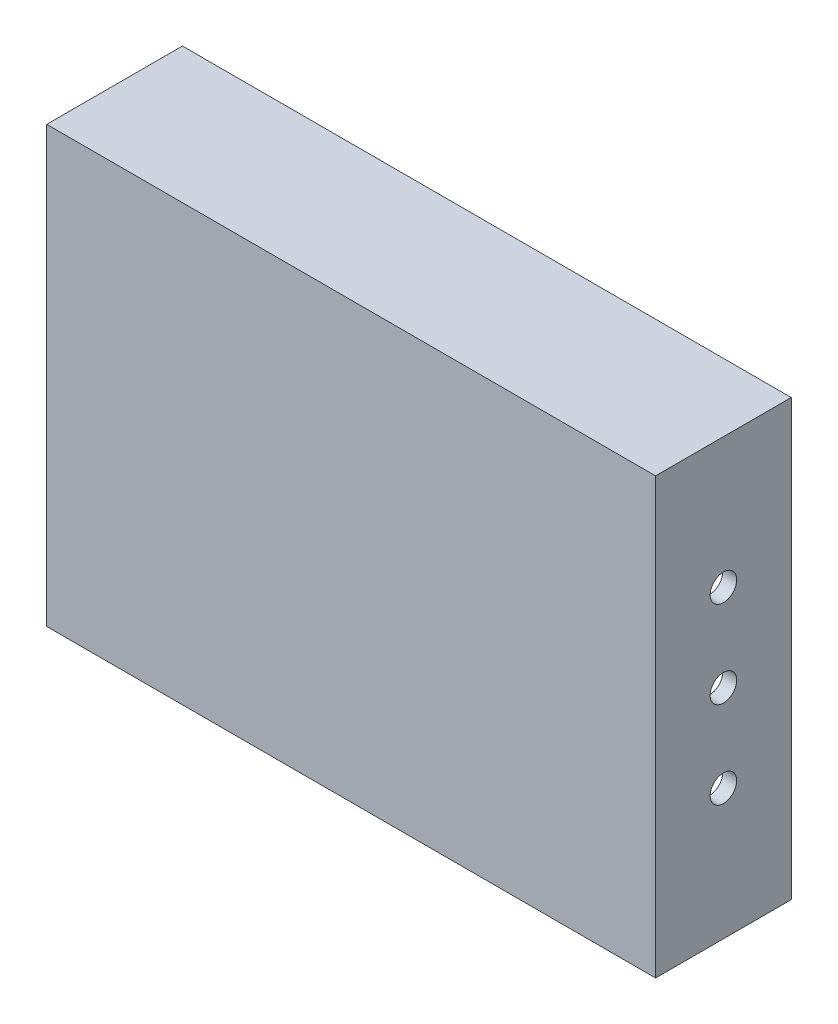
SolidWorks part; units mm, degrees
ref_plane "Front Plane" through (0, 0, 0) normal (0, 0, 1) x (1, 0, 0)
ref_plane "Top Plane" through (0, 0, 0) normal (0, 1, 0) x (1, 0, 0)
ref_plane "Right Plane" through (0, 0, 0) normal (1, 0, 0) x (0, 0, -1)
sketch "Sketch1" plane through (0, 0, 0) normal (0, 0, 1) x (1, 0, 0)
  line L0 (-93.5, 121) -> (-164, 121)
  line L1 (-175, 125) -> (0, 125)
  line L2 (-175, 125) -> (-175, 0)
  line L3 (-175, 0) -> (0, 0)
  line L4 (0, 125) -> (0, 0)
  line L5 (-11, 4) -> (-81.5, 4)
  line L6 (-4, 11) -> (-4, 114)
  line L7 (-11, 121) -> (-81.5, 121)
  line L8 (-171, 11) -> (-171, 114)
  line L11 (-171, 114) -> (-164, 114)
  line L12 (-164, 121) -> (-164, 114)
  line L15 (-171, 11) -> (-164, 11)
  line L16 (-164, 4) -> (-164, 11)
  line L19 (-4, 11) -> (-11, 11)
  line L20 (-11, 4) -> (-11, 11)
  line L23 (-4, 114) -> (-11, 114)
  line L24 (-11, 121) -> (-11, 114)
  line L26 (-93.5, 121) -> (-93.5, 114)
  line L27 (-93.5, 114) -> (-81.5, 114)
  line L28 (-81.5, 121) -> (-81.5, 114)
  line L30 (-93.5, 4) -> (-93.5, 11)
  line L31 (-93.5, 11) -> (-81.5, 11)
  line L32 (-81.5, 4) -> (-81.5, 11)
  line L33 (-93.5, 4) -> (-164, 4)
  dimension "D1" = 4
  dimension "D2" = 4
  dimension "D3" = 4
  dimension "D4" = 4
  dimension "D17" = 7
extrude "Boss-Extrude1" add sketch "Sketch1" along normal blind 35
sketch "Sketch2" plane through (0, 0, 35) normal (0, 0, 1) x (1, 0, 0)
  line L1 (-175, 125) -> (0, 125)
  line L2 (-175, 125) -> (-175, 0)
  line L3 (-175, 0) -> (0, 0)
  line L4 (0, 125) -> (0, 0)
extrude "Boss-Extrude2" add sketch "Sketch2" along normal blind 4
sketch "Sketch3" plane through (0, 0, 0) normal (0, 0, -1) x (-1, 0, 0)
  line L0 (0, 0) -> (0, 125) construction
  line L1 (0, 125) -> (175, 125) construction
  line L2 (175, 125) -> (175, 0) construction
  line L3 (175, 0) -> (0, 0) construction
  circle A0 centre (6, 119) radius 2.045
  circle A1 centre (87.5, 119) radius 2.045
  circle A2 centre (169, 119) radius 2.045
  circle A3 centre (169, 6) radius 2.045
  circle A4 centre (87.5, 6) radius 2.045
  circle A5 centre (6, 6) radius 2.045
  point P20 (87.5, 0)
  point P21 (87.5, 125)
  dimension "D1" = 4.09
  dimension "D4" = 4.09
  dimension "D7" = 4.09
  dimension "D10" = 4.09
  dimension "D13" = 4.09
  dimension "D14" = 4.09
  dimension "D2" = 6
  dimension "D3" = 6
  dimension "D5" = 6
  dimension "D6" = 6
  dimension "D8" = 6
  dimension "D9" = 6
  dimension "D11" = 6
  dimension "D12" = 6
  dimension "D15" = 6
  dimension "D16" = 6
extrude "Cut-Extrude1" cut sketch "Sketch3" against normal blind 6
sketch "Sketch4" plane through (0, 0, 0) normal (1, 0, 0) x (0, 0, -1)
  line L0 (-39, 125) -> (0, 125) construction
  line L1 (-39, 0) -> (-39, 125) construction
  circle A0 centre (-19.5, 87.5) radius 3.81
  circle A1 centre (-19.5, 62.5) radius 3.81
  circle A2 centre (-19.5, 37.5) radius 3.81
  point P6 (0, 0)
  point P9 (-19.5, 125)
  point P10 (0, 0)
  point P12 (-78.7424, 48.6819)
  point P14 (-39, 62.5)
  dimension "D1" = 7.62
  dimension "D2" = 7.62
  dimension "D3" = 7.62
  dimension "D4" = 25
  dimension "D5" = 25
extrude "Cut-Extrude2" cut sketch "Sketch4" against normal blind 10
sketch "Sketch5" plane through (-175, 0, 0) normal (-1, 0, 0) x (0, 0, 1)
  line L0 (39, 125) -> (0, 125) construction
  circle A0 centre (19.5, 100) radius 6
  circle A1 centre (19.5, 75) radius 6.35
  point P2 (0, 0)
  point P5 (19.5, 125)
  dimension "D1" = 12
  dimension "D3" = 12.7
  dimension "D2" = 25
  dimension "D4" = 25
extrude "Cut-Extrude3" cut sketch "Sketch5" against normal blind 10
